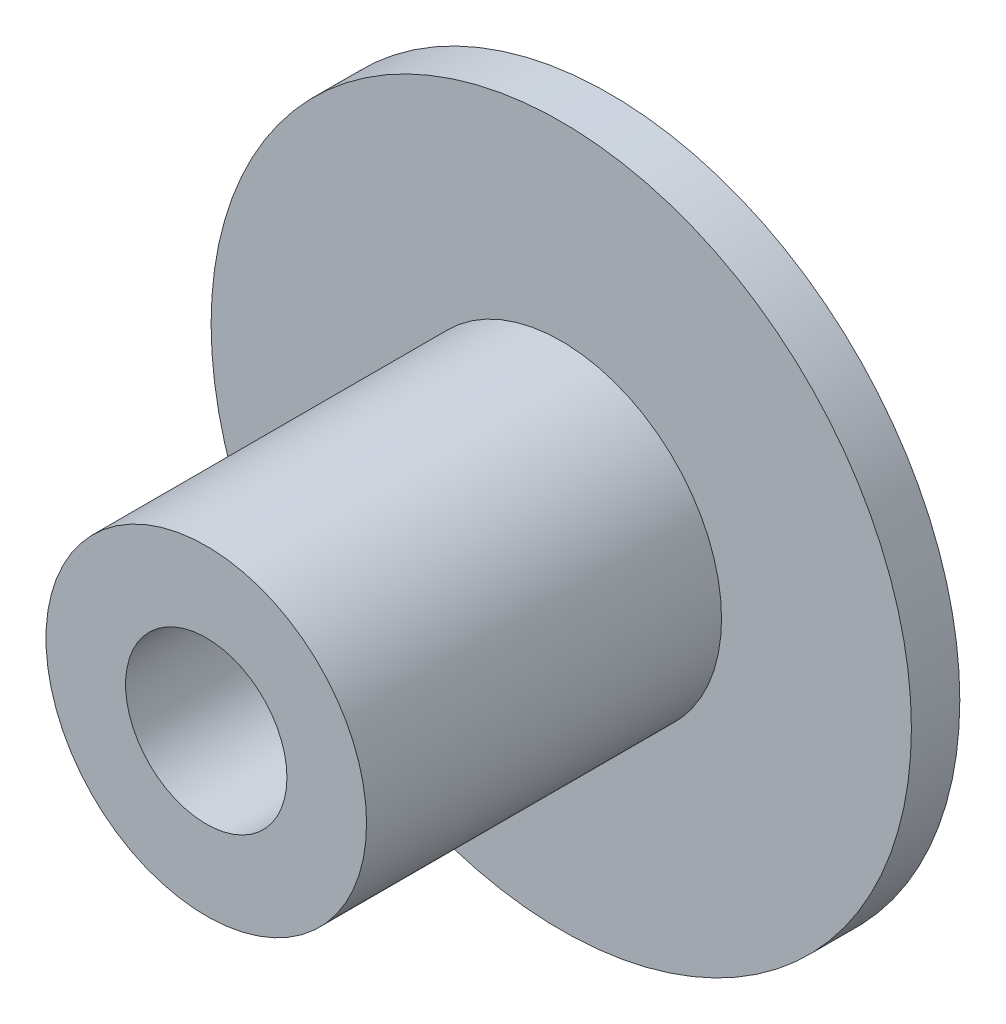
SolidWorks part; units mm, degrees
ref_plane "Front" through (0, 0, 0) normal (0, 0, 1) x (1, 0, 0)
ref_plane "Top" through (0, 0, 0) normal (0, 1, 0) x (1, 0, 0)
ref_plane "Right" through (0, 0, 0) normal (1, 0, 0) x (0, 0, -1)
sketch "Skizze1" plane through (0, 0, 0) normal (0, 0, 1) x (1, 0, 0)
  circle A0 centre (0, 0) radius 32.55
  circle A1 centre (0, 0) radius 7.5
  dimension "D1" = 65.1
  dimension "D2" = 15
extrude "Aufsatz-Linear austragen1" add sketch "Skizze1" along normal blind 4.5
sketch "Skizze2" plane through (0, 0, 4.5) normal (0, 0, 1) x (1, 0, 0)
  circle A0 centre (0, 0) radius 7.5
  circle A1 centre (0, 0) radius 14.9
  circle A2 centre (0, 0) radius 7.5 construction
  dimension "D1" = 29.8
extrude "Aufsatz-Linear austragen2" add sketch "Skizze2" along normal blind 33
